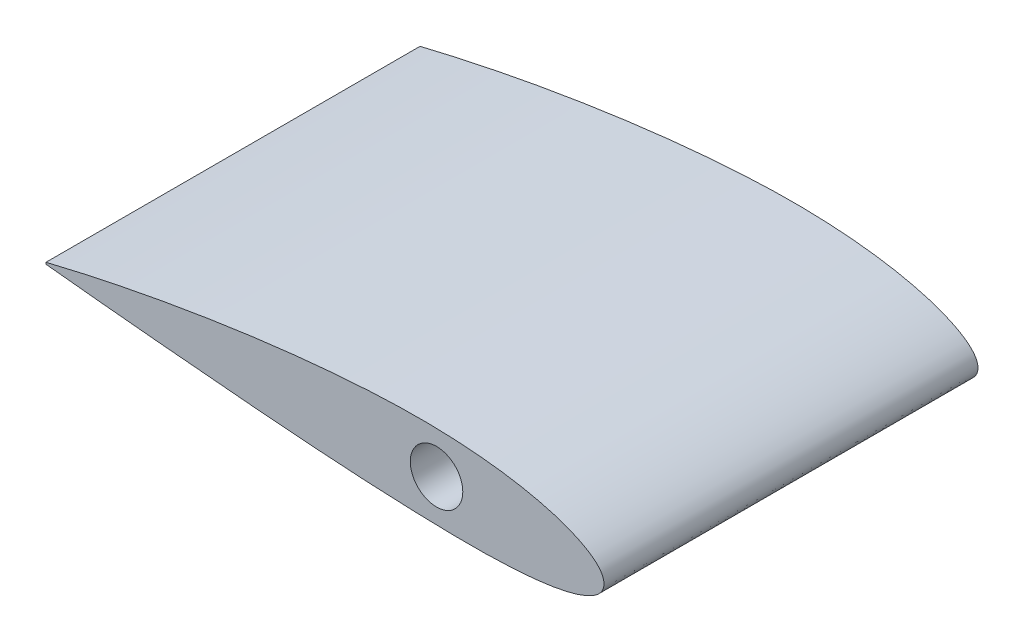
SolidWorks part; units mm, degrees
ref_plane "Front Plane" through (0, 0, 0) normal (0, 0, 1) x (1, 0, 0)
ref_plane "Top Plane" through (0, 0, 0) normal (0, 1, 0) x (1, 0, 0)
ref_plane "Right Plane" through (0, 0, 0) normal (1, 0, 0) x (0, 0, -1)
sketch "Sketch1" plane through (0, 0, 0) normal (0, 0, 1) x (1, 0, 0)
  line L0 (-238.675, 0.3812) -> (-238.675, -0.3751)
  spline S0 degree 3 poles (-238.675, 0.3812) (-238.5621, 0.4088) (-238.0864, 0.525) (-237.0081, 0.7872) (-235.2039, 1.2222) (-232.6924, 1.8199) (-229.488, 2.5698) (-225.609, 3.4587) (-221.0778, 4.4715) (-215.9209, 5.5913) (-210.1682, 6.8003) (-203.8537, 8.0797) (-197.0149, 9.4103) (-189.6924, 10.7725) (-181.9303, 12.1466) (-173.7754, 13.5129) (-165.2772, 14.852) (-156.4875, 16.1441) (-147.4603, 17.3699) (-138.2511, 18.51) (-128.9173, 19.5455) (-119.5168, 20.4576) (-110.1086, 21.229) (-100.7387, 21.8426) (-91.4486, 22.2882) (-82.2958, 22.496) (-73.3548, 22.4639) (-64.7028, 22.1871) (-56.3979, 21.6678) (-48.4959, 20.9122) (-41.0494, 19.9314) (-34.1075, 18.7407) (-27.7153, 17.3594) (-21.9133, 15.8098) (-16.7367, 14.1166) (-12.2152, 12.3056) (-8.3725, 10.4021) (-5.2252, 8.4289) (-2.7832, 6.4015) (-1.0522, 4.3226) (-0.0567, 2.1725) (0.1298, -0.013) (-0.4851, -2.1166) (-1.8739, -4.0278) (-3.9517, -5.7341) (-6.6937, -7.2673) (-10.0887, -8.6373) (-14.1208, -9.8444) (-18.7681, -10.8855) (-24.0034, -11.7578) (-29.7957, -12.4602) (-36.1108, -12.9938) (-42.9122, -13.363) (-50.1607, -13.5749) (-57.8154, -13.64) (-65.8334, -13.5713) (-74.17, -13.3843) (-82.7787, -13.0969) (-91.6286, -12.7253) (-100.6831, -12.2947) (-109.8865, -11.7662) (-119.1666, -11.1621) (-128.454, -10.4982) (-137.6926, -9.7903) (-146.8261, -9.0526) (-155.7985, -8.2981) (-164.5547, -7.538) (-173.0404, -6.7824) (-181.2027, -6.04) (-188.9905, -5.3183) (-196.3547, -4.6241) (-203.2487, -3.9636) (-209.6287, -3.3428) (-215.4538, -2.7672) (-220.6864, -2.2426) (-225.2928, -1.7737) (-229.243, -1.3675) (-232.5108, -1.0239) (-235.0757, -0.761) (-236.9188, -0.5487) (-238.0316, -0.4591) (-238.5336, -0.3746) (-238.6667, -0.3751) (-238.675, -0.3751) knots 0 0 0 0 0.00071 0.002991 0.006776 0.012042 0.018755 0.026873 0.036343 0.047107 0.059098 0.072239 0.08645 0.101642 0.11772 0.134585 0.152133 0.170254 0.188835 0.207762 0.226917 0.24618 0.265434 0.284558 0.303518 0.322224 0.340458 0.35811 0.375077 0.391262 0.406574 0.420931 0.434259 0.446495 0.457587 0.467499 0.476213 0.48374 0.490134 0.495518 0.500134 0.504377 0.50862 0.513229 0.518587 0.524921 0.532344 0.5409 0.550595 0.561407 0.573297 0.586215 0.600101 0.614886 0.630494 0.646843 0.663847 0.681412 0.699441 0.717936 0.736765 0.755733 0.774724 0.793623 0.812313 0.830679 0.848607 0.865984 0.882702 0.898656 0.913744 0.927871 0.940947 0.952887 0.963615 0.97306 0.981161 0.987864 0.993124 0.996907 0.999187 0.999949 1 1 1 1
extrude "Boss-Extrude1" add sketch "Sketch1" along normal mid plane 160
sketch "Sketch2" plane through (0, 0, 0) normal (0, 0, 1) x (1, 0, 0)
  circle A0 centre (-71.603, 4.475) radius 11.2275
extrude "Cut-Extrude1" cut sketch "Sketch2" against normal mid plane 162
